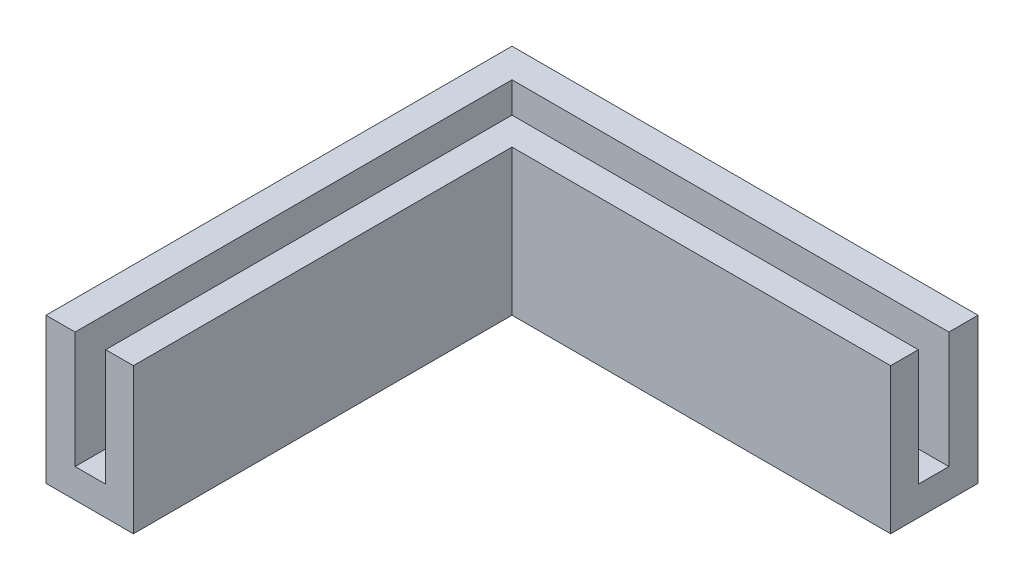
SolidWorks part; units mm, degrees
ref_plane "Front Plane" through (0, 0, 0) normal (0, 0, 1) x (1, 0, 0)
ref_plane "Top Plane" through (0, 0, 0) normal (0, 1, 0) x (1, 0, 0)
ref_plane "Right Plane" through (0, 0, 0) normal (1, 0, 0) x (0, 0, -1)
sketch "Sketch1" plane through (0, 0, 0) normal (0, 1, 0) x (1, 0, 0)
  line L0 (0, 0) -> (32, 0)
  line L1 (32, 0) -> (32, -6)
  line L2 (32, -6) -> (6, -6)
  line L3 (6, -6) -> (6, -32)
  line L4 (6, -32) -> (0, -32)
  line L5 (0, -32) -> (0, 0)
  dimension "D1" = 32
  dimension "D2" = 32
  dimension "D3" = 6
  dimension "D4" = 6
extrude "Boss-Extrude1" add sketch "Sketch1" along normal blind 2
sketch "Sketch2" plane through (0, 2, 0) normal (0, 1, 0) x (1, 0, 0)
  line L0 (2, -32) -> (2, -2)
  line L1 (0, -32) -> (6, -32) construction
  line L2 (2, -2) -> (32, -2)
  line L3 (32, -6) -> (32, 0) construction
  line L4 (32, -4.1) -> (4.1, -4.1)
  line L5 (4.1, -4.1) -> (4.1, -32)
  line L6 (32, 0) -> (0, 0) construction
  line L7 (0, 0) -> (0, -32) construction
  line L8 (6, -6) -> (32, -6) construction
  line L9 (6, -32) -> (6, -6) construction
  line L10 (2, -32) -> (0, -32)
  line L11 (0, -32) -> (0, 0)
  line L12 (0, 0) -> (32, 0)
  line L13 (32, 0) -> (32, -2)
  line L14 (32, -4.1) -> (32, -6)
  line L15 (32, -6) -> (6, -6)
  line L16 (6, -6) -> (6, -32)
  line L17 (6, -32) -> (4.1, -32)
  dimension "D1" = 2
  dimension "D2" = 2
  dimension "D3" = 1.9
  dimension "D4" = 1.9
extrude "Boss-Extrude2" add sketch "Sketch2" along normal blind 8
